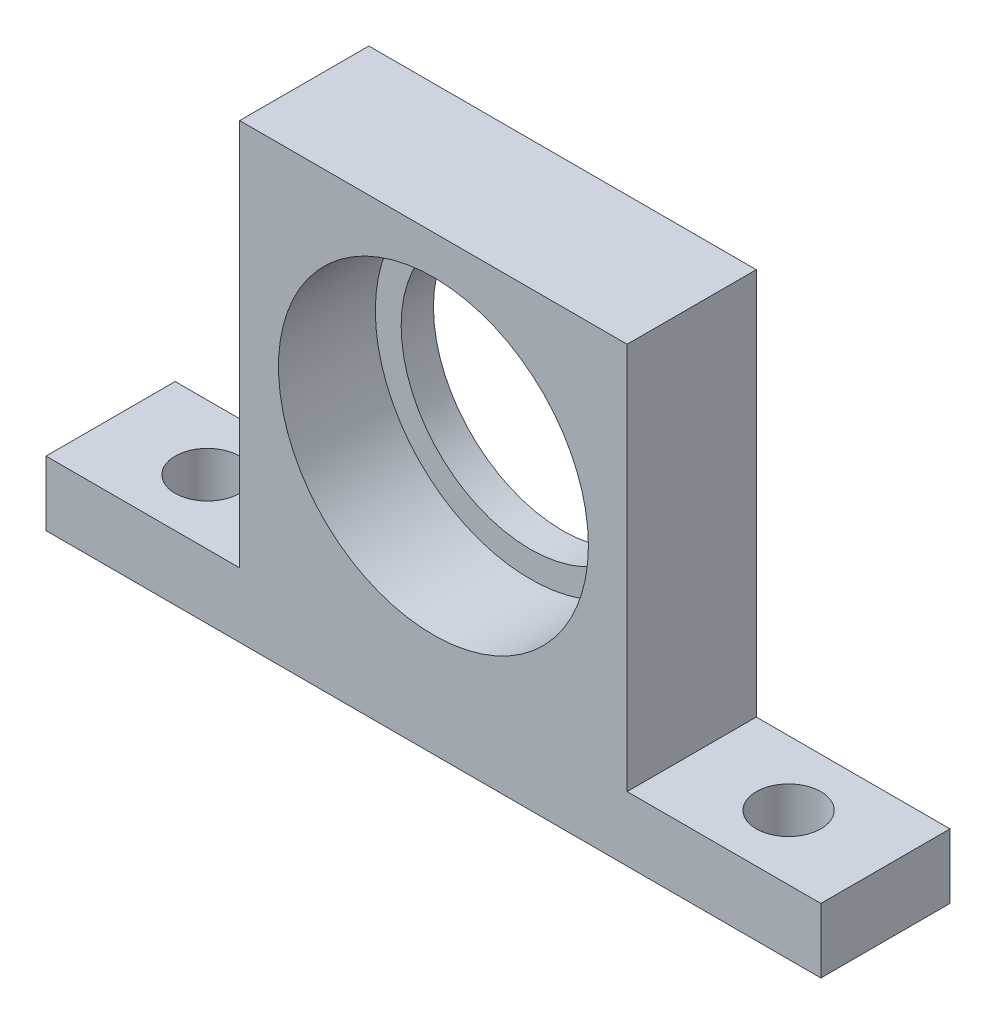
SolidWorks part; units mm, degrees
ref_plane "Front Plane" through (0, 0, 0) normal (0, 0, 1) x (1, 0, 0)
ref_plane "Top Plane" through (0, 0, 0) normal (0, 1, 0) x (1, 0, 0)
ref_plane "Right Plane" through (0, 0, 0) normal (1, 0, 0) x (0, 0, -1)
sketch "Sketch1" plane through (0, 0, 0) normal (0, 0, 1) x (1, 0, 0)
  line L0 (38.1, 0) -> (-38.1, 0)
  line L1 (-38.1, 0) -> (-38.1, 6.35)
  line L2 (-38.1, 6.35) -> (-19.05, 6.35)
  line L3 (-19.05, 6.35) -> (-19.05, 44.45)
  line L4 (-19.05, 44.45) -> (19.05, 44.45)
  line L5 (0, 44.45) -> (0, 0) construction
  line L6 (19.05, 6.35) -> (19.05, 44.45)
  line L7 (38.1, 6.35) -> (19.05, 6.35)
  line L8 (38.1, 0) -> (38.1, 6.35)
  line L9 (-19.05, 25.4) -> (19.05, 25.4) construction
  circle A0 centre (0, 25.4) radius 12.7
  dimension "D5" = 25.4
  dimension "D1" = 6.35
  dimension "D2" = 19.05
  dimension "D3" = 38.1
  dimension "D4" = 19.05
extrude "Boss-Extrude1" add sketch "Sketch1" along normal blind 12.7
sketch "Sketch2" plane through (0, 0, 12.7) normal (0, 0, 1) x (1, 0, 0)
  circle A2 centre (0, 25.4) radius 15.24
  circle A3 centre (0, 25.4) radius 15.24
  dimension "D1" = 2.54
extrude "Cut-Extrude1" cut sketch "Sketch2" against normal offset from surface (9.525 mm away) 3.175 up to face at (0, 14.2875, 0)
hole_wizard "1/4 (0.25) Diameter Hole1" positions "3DSketch1" profile "Sketch4" hole size "1/4" standard "Ansi Inch" end condition through all
sketch3d "3DSketch1"
  line L0 (-38.1, 6.35, 6.35) -> (-19.05, 6.35, 6.35) construction
  line L1 (-38.1, 6.35, 12.7) -> (-38.1, 6.35, 0) construction
  line L2 (-19.05, 6.35, 12.7) -> (-19.05, 6.35, 0) construction
  line L8 (19.05, 6.35, 6.35) -> (38.1, 6.35, 6.35) construction
  line L9 (19.05, 6.35, 12.7) -> (19.05, 6.35, 0) construction
  line L10 (38.1, 6.35, 12.7) -> (38.1, 6.35, 0) construction
  point P0 (-28.575, 6.35, 6.35)
  point P23 (28.575, 6.35, 6.35)
sketch "Sketch4" plane through (-28.575, 6.35, 6.35) normal (1, 0, 0) x (0, 0, 1)
  line L0 (0, 0) -> (0, 6.35)
  line L1 (0, 6.35) -> (3.175, 6.35)
  line L2 (3.175, 6.35) -> (3.175, 0)
  line L5 (3.175, 0) -> (0, 0)
  line L11 (0, -6.35) -> (0, 107.95) construction
  dimension "Thru Hole Dia." = 6.35
  dimension "Thru Hole Depth" = 6.35
